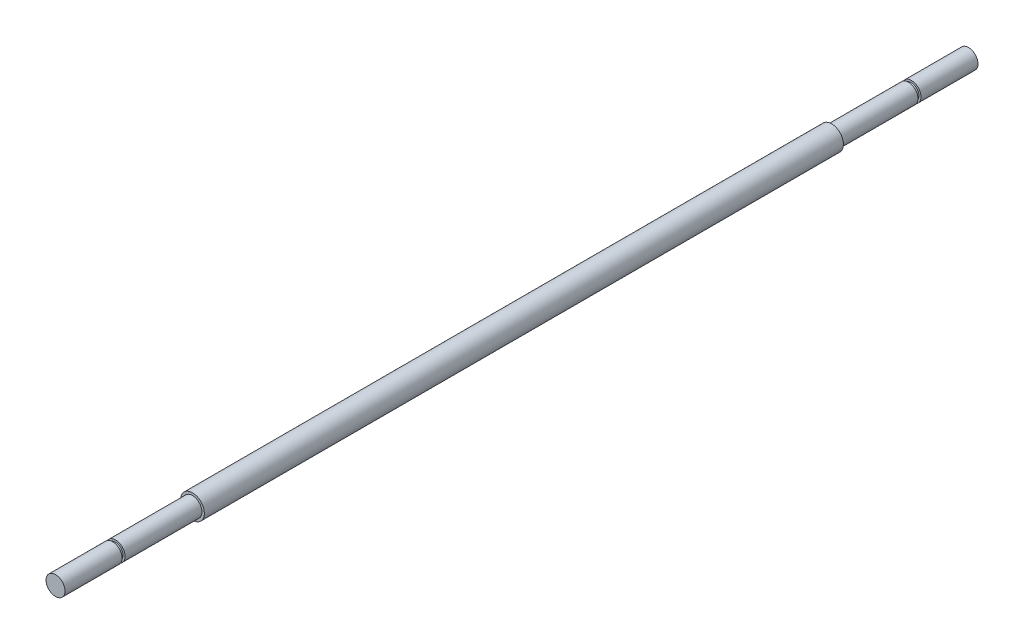
SolidWorks part; units mm, degrees
ref_plane "Front Plane" through (0, 0, 0) normal (0, 0, 1) x (1, 0, 0)
ref_plane "Top Plane" through (0, 0, 0) normal (0, 1, 0) x (1, 0, 0)
ref_plane "Right Plane" through (0, 0, 0) normal (1, 0, 0) x (0, 0, -1)
sketch "Sketch1" plane through (0, 0, 0) normal (0, 0, 1) x (1, 0, 0)
  circle A0 centre (0, 0) radius 7.9375
  dimension "D1" = 15.875
extrude "Boss-Extrude1" add sketch "Sketch1" along normal blind 609.6
fillet "Fillet1" radius 0.25 2 edges at (7.9375, 0, 0) (7.9375, 0, 609.6)
sketch "Sketch2" plane through (0, 0, 0) normal (0, 1, 0) x (1, 0, 0)
  line L0 (7.9375, -609.35) -> (7.9375, -0.25) construction
  line L1 (6.35, -91.44) -> (7.9375, -91.44)
  line L2 (6.35, -91.44) -> (6.35, 0)
  line L3 (6.35, 0) -> (7.9375, 0)
  line L4 (7.9375, -91.44) -> (7.9375, 0)
  line L5 (0, -0.7802) -> (0, -54.9172) construction
  line L7 (7.6875, 0) -> (-7.6875, 0) construction
  point P0 (7.9375, -26.8365)
  dimension "D1" = 6.35
  dimension "D2" = 91.44
revolve "Cut-Revolve2" cut sketch "Sketch2" angle 360 about L5
sketch "Sketch3" plane through (0, 0, 0) normal (0, 1, 0) x (1, 0, 0)
  line L0 (0, 0) -> (0, -609.35) construction
  line L1 (7.9375, -609.35) -> (-7.9375, -609.35) construction
sketch "Sketch4" plane through (0, 0, 0) normal (0, 1, 0) x (1, 0, 0)
  line L0 (6.35, -91.44) -> (6.35, 0) construction
  line L1 (7.6708, -38.1) -> (5.0292, -38.1)
  line L2 (7.6708, -38.1) -> (7.6708, -40.1)
  line L3 (7.6708, -40.1) -> (5.0292, -40.1)
  line L4 (5.0292, -38.1) -> (5.0292, -40.1)
  line L5 (7.6708, -38.1) -> (5.0292, -40.1) construction
  line L6 (7.6708, -40.1) -> (5.0292, -38.1) construction
  line L7 (6.35, 0) -> (-6.35, 0) construction
  line L8 (0, 0) -> (0, -609.35) construction
  point P0 (6.35, -39.1)
  dimension "D1" = 38.1
  dimension "D2" = 2
  dimension "D3" = 5.0292
revolve "Cut-Revolve3" cut sketch "Sketch4" angle 360 about L0
ref_plane "Plane2" through (0, 0, 304.8) normal (0, 0, 1) x (1, 0, 0)
mirror "Mirror1" about plane through (0, 0, 304.8) normal (0, 0, 1) of "Cut-Revolve2", "Cut-Revolve3"
